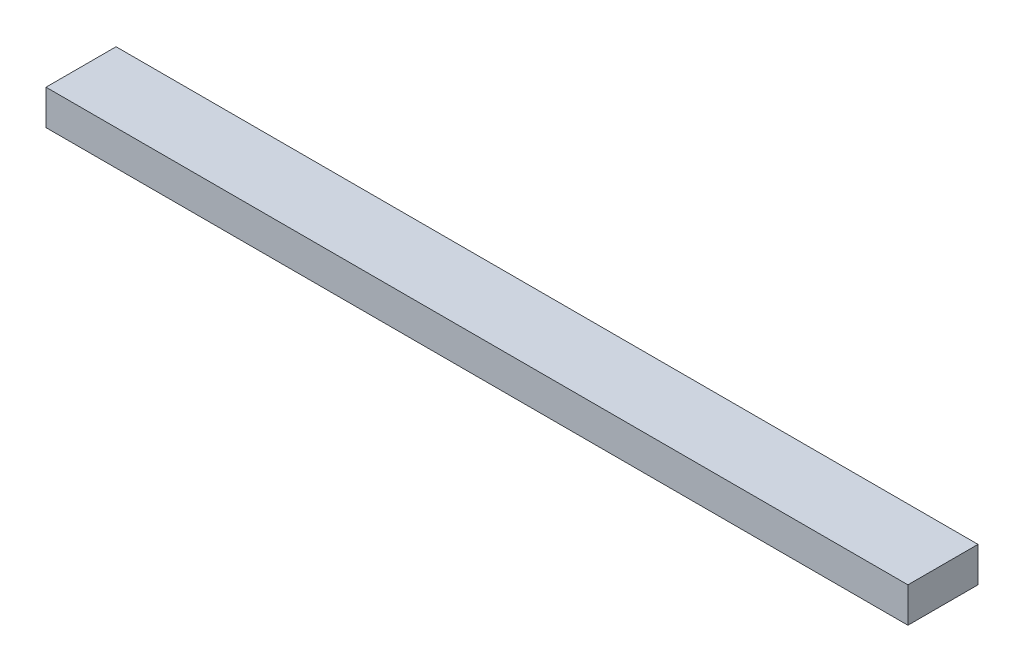
SolidWorks part; units mm, degrees
ref_plane "Спереди" through (0, 0, 0) normal (0, 0, 1) x (1, 0, 0)
ref_plane "Сверху" through (0, 0, 0) normal (0, 1, 0) x (1, 0, 0)
ref_plane "Справа" through (0, 0, 0) normal (1, 0, 0) x (0, 0, -1)
sketch "Эскиз1" plane through (0, 0, 0) normal (0, 1, 0) x (1, 0, 0)
  line L1 (123, 10) -> (-123, 10)
  line L2 (123, 10) -> (123, -10)
  line L3 (123, -10) -> (-123, -10)
  line L4 (-123, 10) -> (-123, -10)
  line L5 (123, 10) -> (-123, -10) construction
  line L6 (123, -10) -> (-123, 10) construction
  point P0 (0, 0)
  dimension "D1" = 246
  dimension "D2" = 20
extrude "Бобышка-Вытянуть1" add sketch "Эскиз1" along normal blind 10
